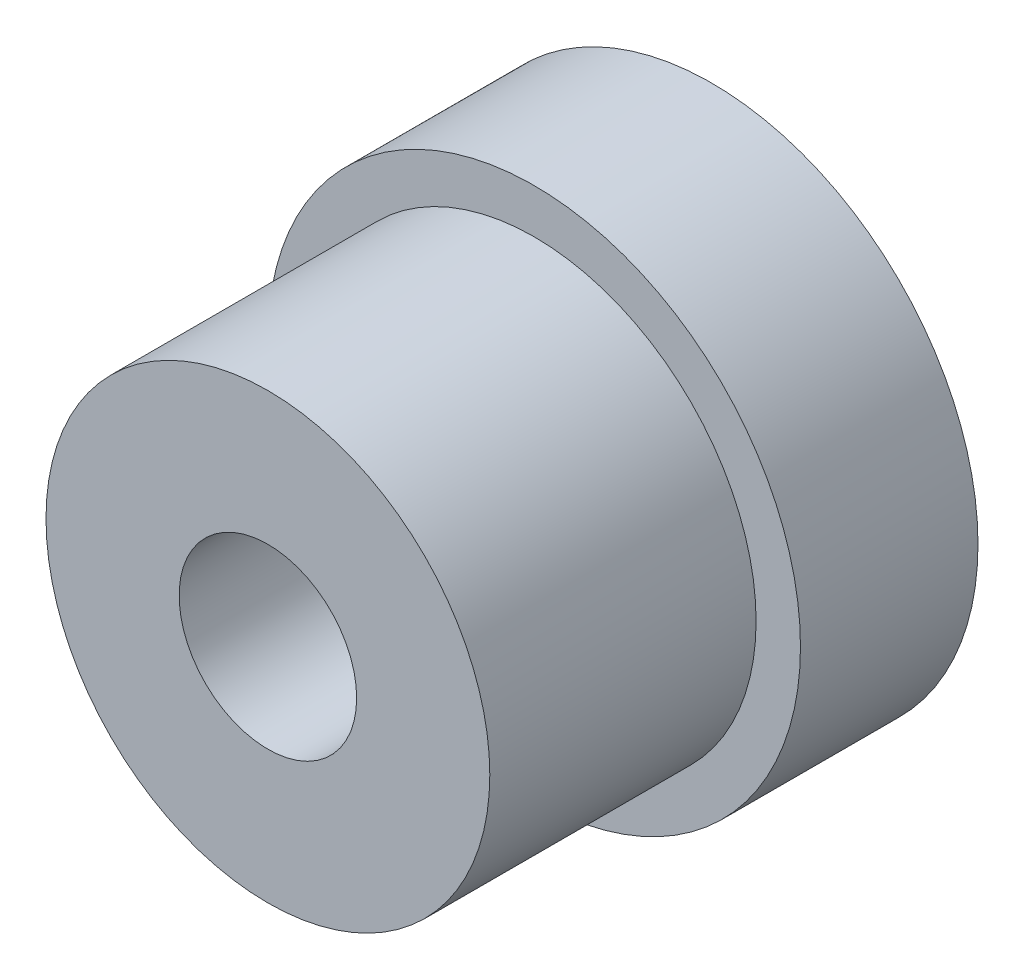
SolidWorks part; units mm, degrees
ref_plane "Front Plane" through (0, 0, 0) normal (0, 0, 1) x (1, 0, 0)
ref_plane "Top Plane" through (0, 0, 0) normal (0, 1, 0) x (1, 0, 0)
ref_plane "Right Plane" through (0, 0, 0) normal (1, 0, 0) x (0, 0, -1)
sketch "Sketch1" plane through (0, 0, 0) normal (0, 0, 1) x (1, 0, 0)
  circle A0 centre (0, 0) radius 4.7625
  dimension "D1" = 9.525
extrude "Boss-Extrude1" add sketch "Sketch1" along normal blind 3.175
sketch "Sketch2" plane through (0, 0, 3.175) normal (0, 0, 1) x (1, 0, 0)
  circle A0 centre (0, 0) radius 3.9688
  dimension "D1" = 7.9375
extrude "Boss-Extrude2" add sketch "Sketch2" along normal blind 4.7625
sketch "Sketch3" plane through (0, 0, 7.9375) normal (0, 0, 1) x (1, 0, 0)
  circle A0 centre (0, 0) radius 1.5875
  dimension "D1" = 3.175
extrude "Cut-Extrude1" cut sketch "Sketch3" against normal through all
